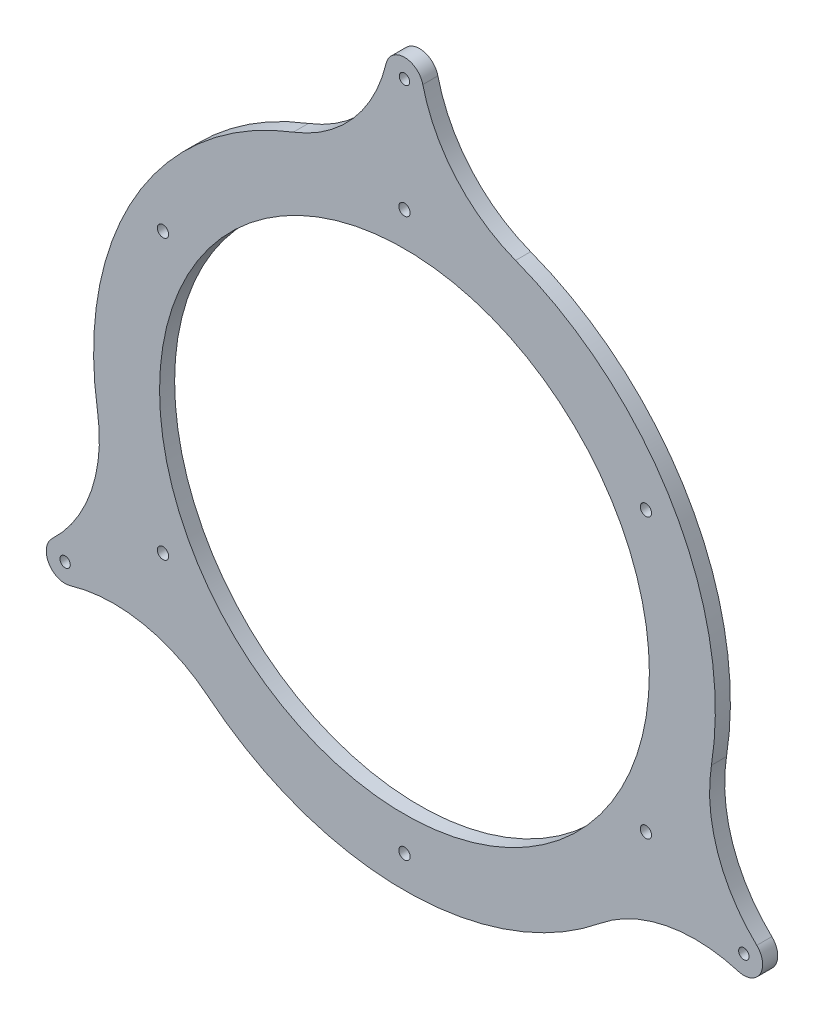
SolidWorks part; units mm, degrees
material "6061-T6 Black anodised"
ref_plane "Front Plane" through (0, 0, 0) normal (0, 0, 1) x (1, 0, 0)
ref_plane "Top Plane" through (0, 0, 0) normal (0, 1, 0) x (1, 0, 0)
ref_plane "Right Plane" through (0, 0, 0) normal (1, 0, 0) x (0, 0, -1)
sketch "Sketch1" plane through (0, 0, 0) normal (0, 0, 1) x (1, 0, 0)
  arc A0 (-29.4841, 77.0515) -> (-81.4706, -12.9918) centre (0, 0) ccw
  circle A1 centre (0, 104) radius 1.375
  arc A2 (4.8644, 105.1567) -> (-4.8644, 105.1567) centre (0, 104) ccw
  arc A3 (4.8644, 105.1567) -> (29.4841, 77.0515) centre (43.7794, 114.4099) ccw
  arc A4 (-4.8644, 105.1567) -> (-29.4841, 77.0515) centre (-43.7794, 114.4099) cw
  arc A5 (93.5005, -48.3657) -> (81.4706, -12.9918) centre (120.9715, -19.2909) cw
  arc A6 (88.6361, -56.791) -> (51.9865, -64.0597) centre (77.1921, -95.119) ccw
  circle A7 centre (90.0666, -52) radius 1.375
  arc A8 (88.6361, -56.791) -> (93.5005, -48.3657) centre (90.0666, -52) ccw
  arc A9 (-88.6361, -56.791) -> (-51.9865, -64.0597) centre (-77.1921, -95.119) cw
  arc A10 (-93.5005, -48.3657) -> (-81.4706, -12.9918) centre (-120.9715, -19.2909) ccw
  circle A11 centre (-90.0666, -52) radius 1.375
  arc A12 (-93.5005, -48.3657) -> (-88.6361, -56.791) centre (-90.0666, -52) ccw
  arc A13 (81.4706, -12.9918) -> (29.4841, 77.0515) centre (0, 0) ccw
  arc A14 (-51.9865, -64.0597) -> (51.9865, -64.0597) centre (0, 0) ccw
  circle A15 centre (0, 92) radius 1.6 construction
  circle A16 centre (79.6743, -46) radius 1.6 construction
  circle A17 centre (-79.6743, -46) radius 1.6 construction
  point P29 (0, 0)
  point P36 (0, 0)
  dimension "D1" = 165
  dimension "D3" = 2.75
  dimension "D4" = 5
  dimension "D5" = 40
  dimension "D8" = 3.2
  dimension "D2" = 104
  dimension "D7" = 92
  dimension "D6" = 3
  dimension "D9" = 3
extrude "Boss-Extrude1" add sketch "Sketch1" along normal blind 4
sketch "Sketch2" plane through (0, 0, 4) normal (0, 0, 1) x (1, 0, 0)
  line L0 (0, 75) -> (64.9519, -37.5) construction
  line L1 (64.9519, -37.5) -> (-64.9519, -37.5) construction
  line L2 (-64.9519, -37.5) -> (0, 75) construction
  line L3 (64.9519, -37.5) -> (0, 0) construction
  line L4 (-64.9519, -37.5) -> (0, 0) construction
  line L5 (0, 75) -> (0, -75) construction
  line L6 (-32.476, 18.75) -> (-64.9519, 37.5) construction
  line L7 (32.476, 18.75) -> (64.9519, 37.5) construction
  line L9 (-37.5, 64.9519) -> (-75, 0)
  line L10 (-75, 0) -> (-37.5, -64.9519)
  line L11 (-37.5, -64.9519) -> (37.5, -64.9519)
  line L12 (37.5, -64.9519) -> (75, 0)
  line L13 (75, 0) -> (37.5, 64.9519)
  line L14 (37.5, 64.9519) -> (-37.5, 64.9519)
  circle A0 centre (0, 0) radius 75 construction
  circle A1 centre (0, 0) radius 75 construction
  point P0 (0, 75)
  point P6 (64.9519, -37.5)
  point P7 (-64.9519, -37.5)
  point P8 (0, 0)
  point P10 (-32.476, 18.75)
  point P11 (32.476, 18.75)
  point P12 (0, -37.5)
  point P18 (32.476, -18.75)
  point P19 (-32.476, -18.75)
  dimension "D1" = 150
  dimension "D3" = 120
  dimension "D4" = 120
  dimension "D5" = 64.9519
  dimension "D6" = 18.75
  dimension "D7" = 32.476
  dimension "D8" = 18.75
  dimension "D9" = 32.476
  dimension "D10" = 37.5
  dimension "D11" = 37.5
  dimension "D12" = 64.9519
  dimension "D13" = 37.5
  dimension "D14" = 75
  dimension "D2" = 3
sketch "Sketch3" plane through (0, 0, 4) normal (0, 0, 1) x (1, 0, 0)
  line L0 (0, 104) -> (0, 0) construction
  line L1 (0, 0) -> (-90.0666, -52) construction
  line L2 (90.0666, -52) -> (0, 0) construction
  circle A0 centre (0, 0) radius 74 construction
  circle A1 centre (0, 74) radius 1.5
  circle A2 centre (-64.0859, -37) radius 1.5
  circle A3 centre (64.0859, -37) radius 1.5
  circle A4 centre (-64.0859, 37) radius 1.5
  circle A5 centre (64.0859, 37) radius 1.5
  circle A6 centre (0, -74) radius 1.5
  circle A7 centre (0, 0) radius 65
  dimension "D1" = 3
  dimension "D2" = 148
  dimension "D3" = 130
extrude "Cut-Extrude1" cut sketch "Sketch3" against normal through all
